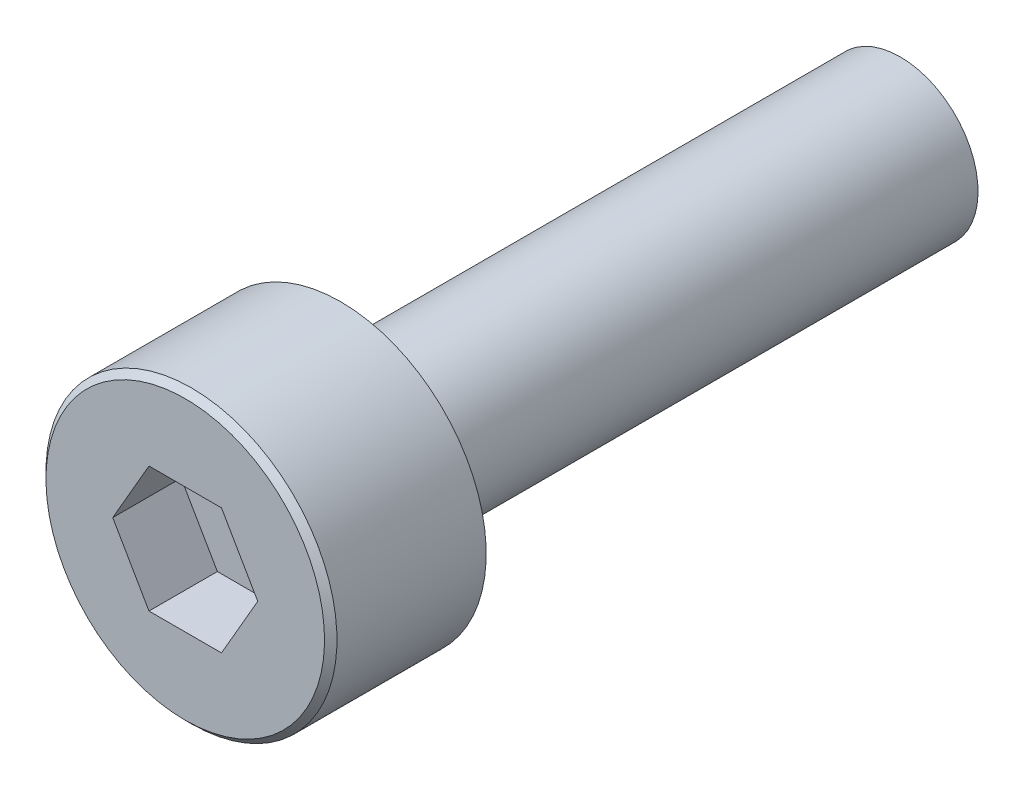
SolidWorks part; units mm, degrees
material "普通碳钢"
ref_plane "前视基准面" through (0, 0, 0) normal (0, 0, 1) x (1, 0, 0)
ref_plane "上视基准面" through (0, 0, 0) normal (0, 1, 0) x (1, 0, 0)
ref_plane "右视基准面" through (0, 0, 0) normal (1, 0, 0) x (0, 0, -1)
sketch "草图1" plane through (0, 0, 0) normal (1, 0, 0) x (0, 0, -1)
  line L0 (0, 0) -> (0, 2.34)
  line L1 (0, 2.34) -> (2.5, 2.34)
  line L2 (2.5, 2.34) -> (2.5, 1.25)
  line L3 (2.5, 1.25) -> (11.5, 1.25)
  line L4 (11.5, 1.25) -> (11.5, 0)
  line L5 (11.5, 0) -> (0, 0) construction
  line L6 (0, 0) -> (11.5, 0)
  dimension "D1" = 4.68
  dimension "D2" = 2.5
  dimension "D3" = 2.5
  dimension "D4" = 9
revolve "旋转1" add sketch "草图1" angle 360 about L5
cosmetic thread "装饰螺纹线1" parameters "D2"=2.459
sketch "草图2" plane through (0, 0, 0) normal (0, 0, 1) x (1, 0, 0)
  line L1 (0.5831, 1.01) -> (-0.5831, 1.01)
  line L2 (-0.5831, 1.01) -> (-1.1662, 0)
  line L3 (-1.1662, 0) -> (-0.5831, -1.01)
  line L4 (-0.5831, -1.01) -> (0.5831, -1.01)
  line L5 (0.5831, -1.01) -> (1.1662, 0)
  line L6 (1.1662, 0) -> (0.5831, 1.01)
  circle A0 centre (0, 0) radius 1.01 construction
  dimension "D1" = 2.02
extrude "切除-拉伸1" cut sketch "草图2" against normal blind 1.1
chamfer "装饰倒角" distance 0.1 angle 45 1 edges at (0, 2.34, 0)
